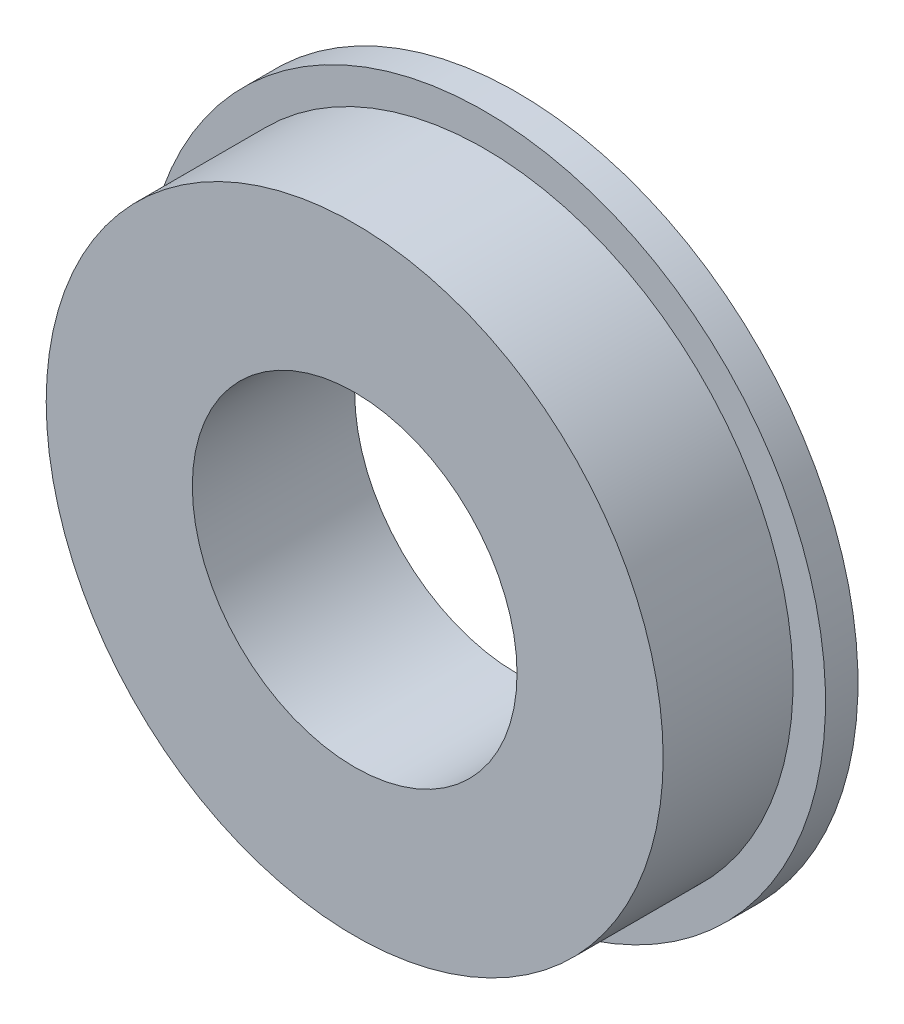
SolidWorks part; units mm, degrees
material "镀铬不锈钢"
ref_plane "前视基准面" through (0, 0, 0) normal (0, 0, 1) x (1, 0, 0)
ref_plane "上视基准面" through (0, 0, 0) normal (0, 1, 0) x (1, 0, 0)
ref_plane "右视基准面" through (0, 0, 0) normal (1, 0, 0) x (0, 0, -1)
sketch "草图1" plane through (0, 0, 0) normal (0, 0, 1) x (1, 0, 0)
  circle A0 centre (0, 0) radius 5
  circle A1 centre (0, 0) radius 9.5
  dimension "D1" = 10
  dimension "D2" = 19
extrude "凸台-拉伸1" add sketch "草图1" along normal blind 5
sketch "草图2" plane through (0, 0, 0) normal (0, 0, -1) x (-1, 0, 0)
  circle A0 centre (0, 0) radius 5
  circle A1 centre (0, 0) radius 10.5
  dimension "D1" = 21
extrude "凸台-拉伸2" add sketch "草图2" against normal blind 1
